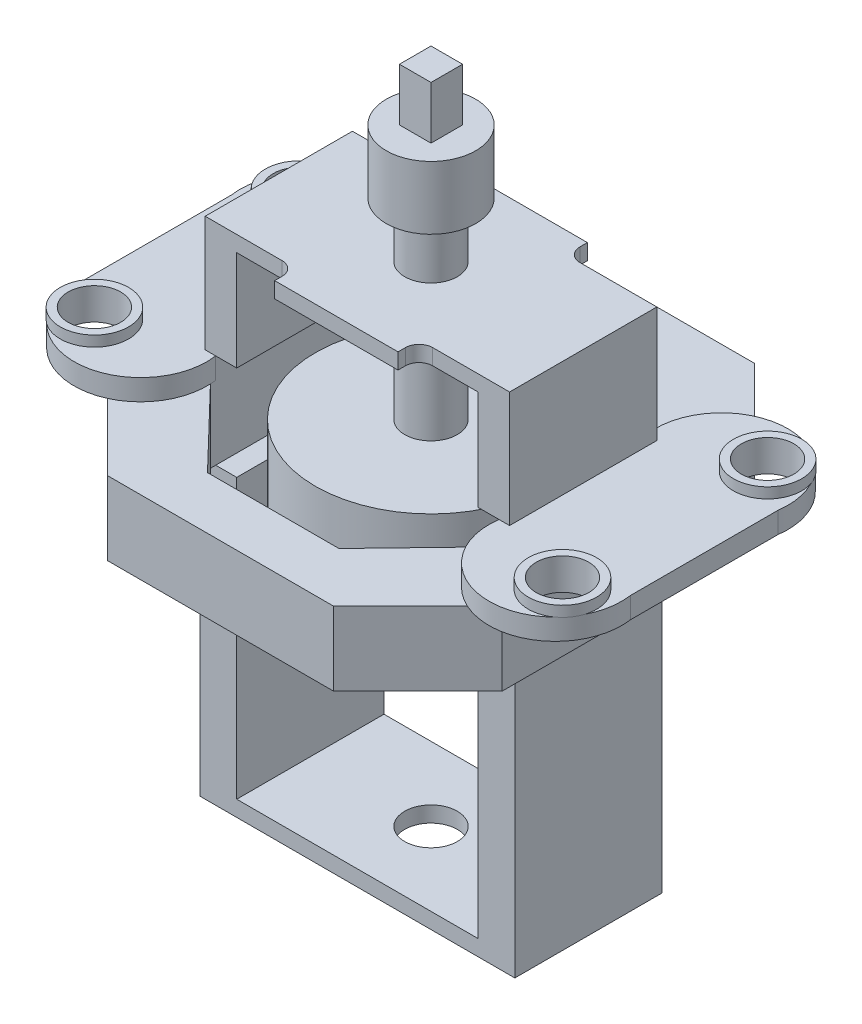
SolidWorks part; units mm, degrees
ref_plane "Alzado" through (0, 0, 0) normal (0, 0, 1) x (1, 0, 0)
ref_plane "Planta" through (0, 0, 0) normal (0, 1, 0) x (1, 0, 0)
ref_plane "Vista lateral" through (0, 0, 0) normal (1, 0, 0) x (0, 0, -1)
sketch "Croquis2" plane through (0, 0, 0) normal (0, 1, 0) x (1, 0, 0)
  line L0 (0, 0) -> (43, 0)
  line L3 (48.44, -55) -> (48.44, -25)
  line L4 (9, -10) -> (34, -10)
  line L5 (21.5, -80) -> (0, -80)
  line L6 (0, -80) -> (43, -80)
  line L7 (59, -64) -> (59, -16)
  line L8 (59, -16) -> (43, 0)
  line L9 (-16, -16) -> (0, 0)
  line L10 (-16, -64) -> (-16, -16)
  line L11 (-16, -64) -> (0, -80)
  line L12 (59, -64) -> (43, -80)
  line L13 (0, -80) -> (43, -80)
  line L14 (34, -10) -> (48.44, -25)
  line L15 (9, -70) -> (34, -70)
  line L16 (34, -70) -> (48.44, -55)
  line L17 (9, -70) -> (-5.44, -55)
  line L18 (9, -10) -> (-5.44, -25)
  line L19 (-5.44, -25) -> (-5.44, -55)
  point P20 (21.5, -70)
extrude "Saliente-Extruir1" add sketch "Croquis2" along normal blind 14 contours L12 L7 L8 L0 L9 L10 L11 L5 L6 L19 L18 L4 L14 L3 L16 L15 L17
sketch "Croquis4" plane through (0, 14, 0) normal (0, 1, 0) x (1, 0, 0)
  circle A0 centre (21.5, -40) radius 22
  dimension "D1" = 44
extrude "Saliente-Extruir2" add sketch "Croquis4" against normal blind 15 separate body
sketch "Croquis5" plane through (0, 14, 0) normal (0, 1, 0) x (1, 0, 0)
  line L0 (-30.44, -26) -> (-30.44, -54)
  line L2 (48.44, -26) -> (48.44, -54)
  line L3 (73.44, -26) -> (73.44, -54)
  line L5 (-5.44, -26) -> (-5.44, -54)
  arc A0 (48.44, -26) -> (73.44, -26) centre (60.94, -24.2105) cw
  circle A1 centre (66, -20.5) radius 5
  circle A2 centre (66, -59.5) radius 5
  arc A3 (48.44, -54) -> (73.44, -54) centre (60.94, -55.7895) ccw
  arc A4 (-5.44, -54) -> (-30.44, -54) centre (-17.94, -55.7895) cw
  circle A5 centre (-23, -59.5) radius 5
  circle A6 centre (-23, -20.5) radius 5
  arc A7 (-5.44, -26) -> (-30.44, -26) centre (-17.94, -24.2105) ccw
  dimension "D1" = 10
extrude "Saliente-Extruir3" add sketch "Croquis5" along normal blind 4
sketch "Croquis7" plane through (0, 18, 0) normal (0, 1, 0) x (1, 0, 0)
  circle A0 centre (-23, -20.5) radius 5
  circle A1 centre (-23, -20.5) radius 6.5
  circle A2 centre (-23, -59.5) radius 5
  circle A3 centre (-23, -59.5) radius 6.5
  circle A4 centre (66, -59.5) radius 6.5
  circle A5 centre (66, -59.5) radius 5
  circle A6 centre (66, -20.5) radius 6.5
  circle A7 centre (66, -20.5) radius 5
  dimension "D1" = 13
extrude "Saliente-Extruir4" add sketch "Croquis7" along normal blind 2
sketch "Croquis8" plane through (0, 18, 0) normal (0, 1, 0) x (1, 0, 0)
  line L1 (-5.44, -26) -> (-1.44, -26)
  line L2 (-5.44, -54) -> (-1.44, -54)
  line L3 (-1.44, -54) -> (-1.44, -26)
  line L4 (-5.44, -26) -> (-7.44, -26)
  line L5 (-7.44, -26) -> (-7.44, -54)
  line L6 (-7.44, -54) -> (-5.44, -54)
  line L7 (50.44, -54) -> (48.44, -54)
  line L8 (50.44, -26) -> (50.44, -54)
  line L9 (48.44, -26) -> (50.44, -26)
  line L10 (44.44, -54) -> (44.44, -26)
  line L11 (48.44, -54) -> (44.44, -54)
  line L12 (48.44, -26) -> (44.44, -26)
extrude "Saliente-Extruir5" add sketch "Croquis8" along normal blind 19
sketch "Croquis9" plane through (0, 37, 0) normal (0, 1, 0) x (1, 0, 0)
  line L0 (-7.44, -26) -> (7.1735, -26)
  line L1 (50.44, -26) -> (50.44, -54)
  line L2 (50.44, -54) -> (35.8265, -54)
  line L3 (-7.44, -54) -> (-7.44, -26)
  line L4 (35.8265, -26) -> (50.44, -26)
  line L5 (9.7721, -23.4014) -> (9.7721, -22.001)
  line L6 (9.7721, -22.001) -> (33.2279, -22.001)
  line L7 (33.2279, -23.4014) -> (33.2279, -22.001)
  line L8 (7.1735, -54) -> (-7.44, -54)
  line L9 (33.2279, -56.5986) -> (33.2279, -57.999)
  line L10 (9.7721, -57.999) -> (33.2279, -57.999)
  line L11 (9.7721, -56.5986) -> (9.7721, -57.999)
  circle A0 centre (21.5, -40) radius 5
  arc A1 (7.1735, -54) -> (9.7721, -56.5986) centre (7.1735, -56.5986) cw
  arc A2 (33.2279, -56.5986) -> (35.8265, -54) centre (35.8265, -56.5986) cw
  arc A3 (35.8265, -26) -> (33.2279, -23.4014) centre (35.8265, -23.4014) cw
  arc A4 (9.7721, -23.4014) -> (7.1735, -26) centre (7.1735, -23.4014) cw
  point P16 (21.5, -22.001)
  point P22 (21.5, -57.999)
  dimension "D1" = 10
  dimension "D2" = 2.5986
extrude "Saliente-Extruir6" add sketch "Croquis9" along normal blind 3
sketch "Croquis10" plane through (0, 14, 0) normal (0, 1, 0) x (1, 0, 0)
  circle A0 centre (21.5, -40) radius 5
extrude "Saliente-Extruir7" add sketch "Croquis10" along normal blind 36.5
sketch "Croquis12" plane through (0, 50.5, 0) normal (0, 1, 0) x (1, 0, 0)
  circle A0 centre (21.5, -40) radius 8.5
  dimension "D1" = 17
extrude "Saliente-Extruir8" add sketch "Croquis12" along normal blind 12
sketch "Croquis13" plane through (0, 0, 0) normal (0, -1, 0) x (1, 0, 0)
  line L0 (-5.44, 54) -> (-1.44, 54)
  line L2 (-1.44, 54) -> (-1.44, 26)
  line L3 (48.44, 54) -> (51.44, 54)
  line L4 (51.44, 54) -> (51.44, 26)
  line L5 (-1.44, 26) -> (-5.44, 26)
  line L6 (-5.44, 26) -> (-8.44, 26)
  line L7 (-8.44, 26) -> (-8.44, 54)
  line L8 (-8.44, 54) -> (-5.44, 54)
  line L9 (48.44, 54) -> (44.44, 54)
  line L10 (44.44, 54) -> (44.44, 26)
  line L11 (44.44, 26) -> (51.44, 26)
  dimension "D1" = 3
  dimension "D2" = 3
extrude "Saliente-Extruir9" add sketch "Croquis13" along normal blind 53
sketch "Croquis14" plane through (0, -53, 0) normal (0, -1, 0) x (1, 0, 0)
  line L0 (-8.44, 54) -> (51.44, 54)
  line L1 (51.44, 54) -> (51.44, 26)
  line L2 (51.44, 26) -> (-8.44, 26)
  line L3 (-8.44, 26) -> (-8.44, 54)
  circle A0 centre (21.5, 40) radius 5
  dimension "D1" = 10
extrude "Saliente-Extruir10" add sketch "Croquis14" along normal blind 3
sketch "Croquis15" plane through (0, 62.5, 0) normal (0, 1, 0) x (1, 0, 0)
  line L1 (21.5, -37) -> (18.5, -37)
  line L2 (18.5, -37) -> (18.5, -43)
  line L3 (18.5, -43) -> (24.5, -43)
  line L4 (24.5, -43) -> (24.5, -37)
  line L5 (24.5, -37) -> (21.5, -37)
  dimension "D2" = 3
  dimension "D3" = 6
  dimension "D4" = 6
extrude "Saliente-Extruir11" add sketch "Croquis15" along normal blind 10
